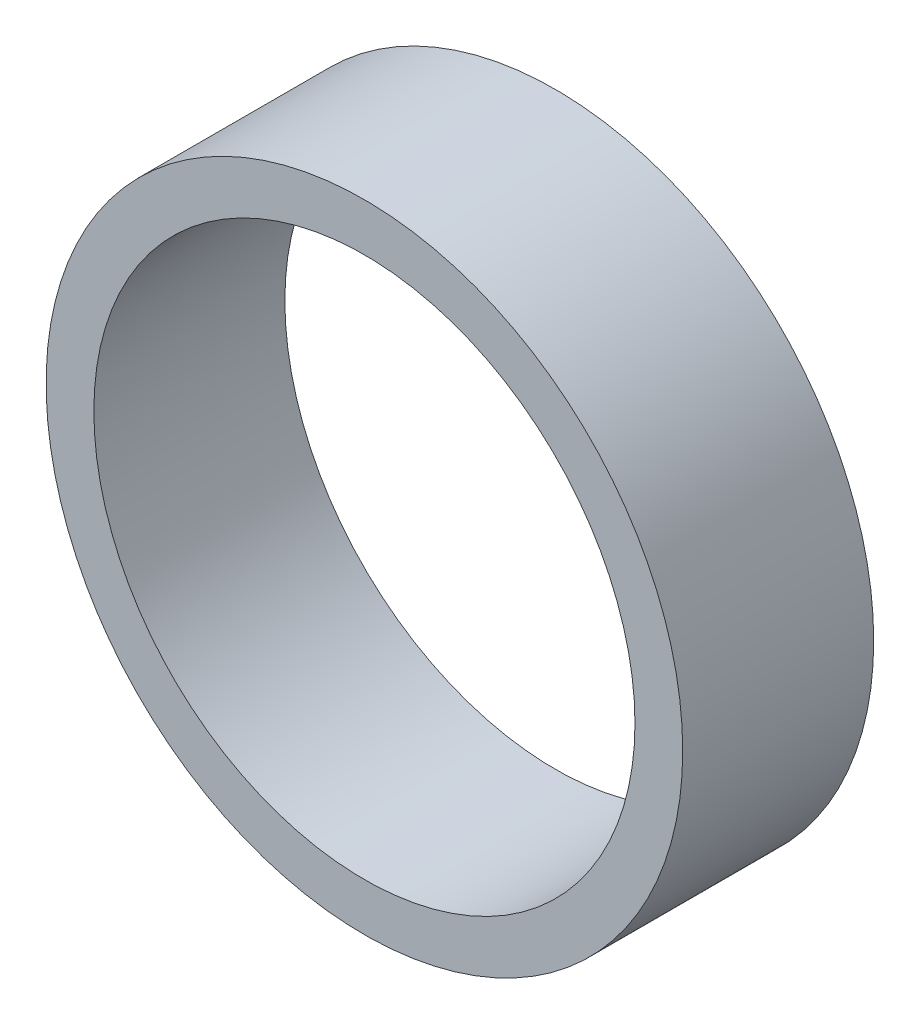
SolidWorks part; units mm, degrees
ref_plane "Front Plane" through (0, 0, 0) normal (0, 0, 1) x (1, 0, 0)
ref_plane "Top Plane" through (0, 0, 0) normal (0, 1, 0) x (1, 0, 0)
ref_plane "Right Plane" through (0, 0, 0) normal (1, 0, 0) x (0, 0, -1)
sketch "Sketch1" plane through (0, 0, 0) normal (0, 0, 1) x (1, 0, 0)
  circle A0 centre (0, 0) radius 10
  circle A1 centre (0, 0) radius 8.5
  dimension "D1" = 20
  dimension "D2" = 17
extrude "Boss-Extrude1" add sketch "Sketch1" along normal blind 6
